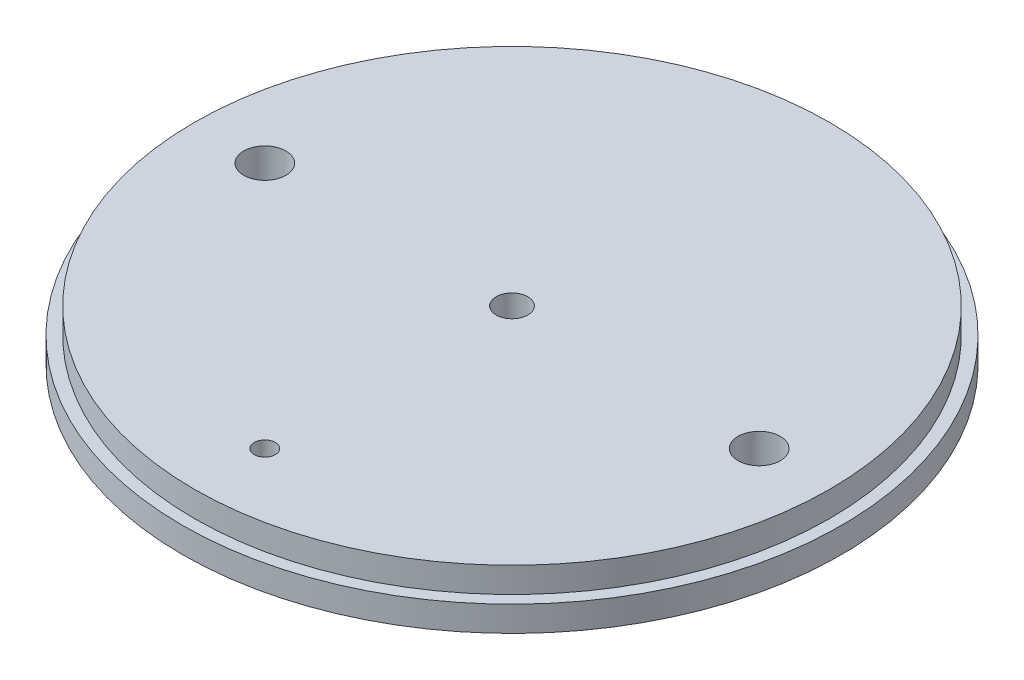
SolidWorks part; units mm, degrees
ref_plane "Front Plane" through (0, 0, 0) normal (0, 0, 1) x (1, 0, 0)
ref_plane "Top Plane" through (0, 0, 0) normal (0, 1, 0) x (1, 0, 0)
ref_plane "Right Plane" through (0, 0, 0) normal (1, 0, 0) x (0, 0, -1)
sketch "Sketch2" plane through (0, 0, 0) normal (0, 1, 0) x (1, 0, 0)
  circle A0 centre (0, 0) radius 49.53
  dimension "D1" = 99.06
extrude "Boss-Extrude1" add sketch "Sketch2" along normal blind 3.81
sketch "Sketch3" plane through (0, 3.81, 0) normal (0, 1, 0) x (1, 0, 0)
  circle A0 centre (0, 0) radius 47.752
  dimension "D1" = 95.504
extrude "Boss-Extrude2" add sketch "Sketch3" along normal blind 3.81
sketch "Sketch5" plane through (0, 0, 0) normal (0, -1, 0) x (1, 0, 0)
  circle A0 centre (0, 0) radius 37.1475
  circle A1 centre (37.1475, 0) radius 3.175
  circle A2 centre (-37.1475, 0) radius 3.175
  circle A3 centre (0, 37.1475) radius 1.5875
  circle A4 centre (0, 0) radius 2.3813
  dimension "D1" = 74.295
  dimension "D2" = 4.7625
  dimension "D3" = 6.35
  dimension "D4" = 3.175
  dimension "D5" = 6.35
extrude "Cut-Extrude1" cut sketch "Sketch5" against normal blind 17.526 contours A0 A1 | A0 A1 | A0 A2 | A0 A2 | A0 A3 | A0 A3 | A4
